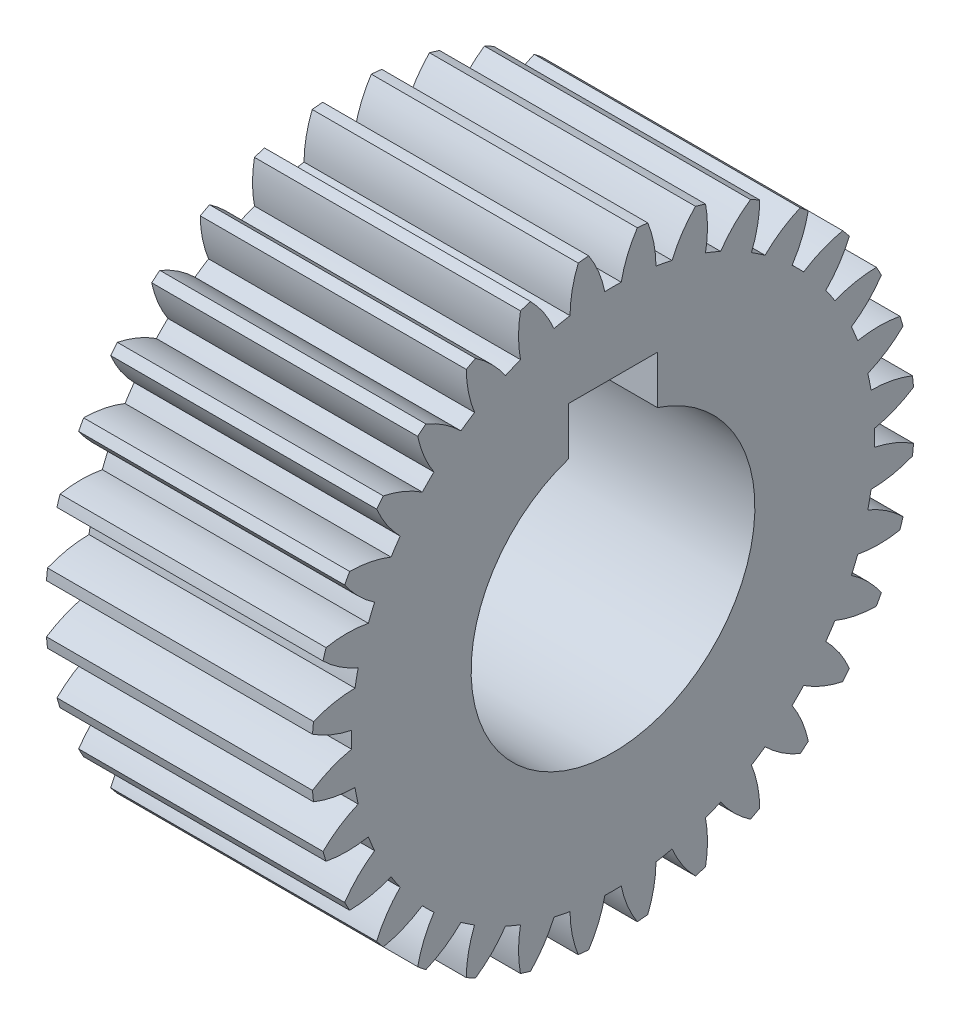
SolidWorks part; units mm, degrees
ref_plane "Plane1" through (0, 0, 0) normal (0, 0, 1) x (1, 0, 0)
ref_plane "Plane2" through (0, 0, 0) normal (0, 1, 0) x (1, 0, 0)
ref_plane "Plane3" through (0, 0, 0) normal (1, 0, 0) x (0, 0, -1)
sketch "HoldingSke" plane through (0, 0, 0) normal (0, 1, 0) x (1, 0, 0)
  line L0 (0, 0) -> (0.848, -0.5299)
  line L1 (-15, 0) -> (100, 0) construction
  line L2 (0, 0) -> (-2.1039, 2.3779)
  line L3 (0, 0) -> (-11.863, 4.5341)
  line L4 (0, 0) -> (7.3237, 4.5764)
  line L5 (0, 0) -> (-46.8476, -17.4728)
  line L6 (0, 0) -> (-12.4344, -8.3896)
  line L7 (-2.1039, 2.3779) -> (8.6586, 51.2059)
  line L8 (-76.2, 54.61) -> (-73.9, 54.61)
  line L9 (-71.009, 38.7566) -> (-53.1078, 45.2721)
  line L10 (-76.2, 71.12) -> (104.1128, 71.12)
  line L11 (0, 0) -> (-15, 0)
  line L12 (-76.2, 101.6) -> (-76.162, 101.6)
  line L13 (24.9733, 27.94) -> (52.9518, 28.4284)
  line L14 (24.9733, 27.94) -> (24.9743, 27.94)
  line L15 (24.9733, 27.94) -> (100.4006, 29.5858)
  line L16 (-63.627, -1) -> (-12.827, -1)
  circle A0 centre (0, 0) radius 8
  circle A1 centre (0, 0) radius 14.749
  circle A2 centre (0, 0) radius 37.5
  circle A3 centre (0, 0) radius 8
  dimension "MHD" = 29.498
  dimension "Hub_dia" = 75
  dimension "Bore" = 16
  dimension "MBD" = 16
  dimension "Num_teeth" = 32
  dimension "Pitch" = 1
  dimension "Overall_len" = 50
  dimension "Show_teeth" = 32
  dimension "Thickness" = 15
  dimension "OAL" = 50.0001
  dimension "T_dim" = 2.3
  dimension "Ap" = 20
  dimension "H" = 19.05
  dimension "Pitch_radius" = 180.3128
  dimension "Width" = 15
  dimension "Backlash" = 0.038
  dimension "Addendum_fac" = 1
  dimension "Dedendum_fac" = 1.25
  dimension "Clearance_fac" = 0.25
  dimension "Dedendum_add" = 0.001
  dimension "Module" = 1
sketch "BasProSke" plane through (0, 0, 0) normal (0, 1, 0) x (1, 0, 0)
  line L0 (-10, 0) -> (60, 0) construction
  line L1 (0, 0) -> (0, 17)
  line L2 (0, 0) -> (15, 0)
  line L3 (15, 0) -> (15, 17)
  line L4 (15, 17) -> (0, 17)
  dimension "Thickness" = 15
  dimension "Diameter" = 34
revolve "Base-Revolve" add sketch "BasProSke" angle 360 about L0
sketch "TooCutSke" plane through (0, 0, 0) normal (1, 0, 0) x (0, 0, -1)
  line L1 (0, 0) -> (0, 107) construction
  line L2 (0, 0) -> (-0.8516, 15.9773) construction
  line L3 (0, 0) -> (-3.1334, 31.8138) construction
  line L4 (-0.8516, 15.9773) -> (-1.5667, 15.9069) construction
  arc A0 (0.462, 14.7418) -> (-0.462, 14.7418) centre (0, 0) ccw
  arc A1 (1.3867, 16.9688) -> (-1.3867, 16.9688) centre (0, 0) ccw
  circle A2 centre (0, 0) radius 16 construction
  circle A3 centre (0, 0) radius 15.0351 construction
  arc A4 (-0.462, 14.7418) -> (-1.3867, 16.9688) centre (-6.7293, 13.4451) ccw
  arc A5 (1.3867, 16.9688) -> (0.462, 14.7418) centre (6.7293, 13.4451) ccw
  dimension "Root_dia" = 29.498
  dimension "Overcut_dia" = 34.0508
  dimension "Pitch_dia" = 32
  dimension "Base_dia" = 30.0702
  dimension "Flank_rad" = 6.4
  dimension "Half_ang" = 5.625
  dimension "Half_CT" = 0.7186
extrude "ToothCut" cut sketch "TooCutSke" along normal through all
fillet "Breaks" [suppressed] radius 0.02
fillet "RootFillets" [suppressed] radius 0.251
pattern_circular "TeethCuts" count 32 every 11.25 about axis through (-10, 0, 0) along (1, 0, 0) of "ToothCut", "RootFillets", "Breaks"
sketch "HubNeaOneSke" plane through (0, 0, 0) normal (-1, 0, 0) x (0, 0, 1)
  circle A0 centre (0, 0) radius 14.749
  dimension "Diameter" = 29.498
extrude "HubNearOne" [suppressed] add sketch "HubNeaOneSke" along normal blind 35.0001
sketch "HubNeaBotSke" plane through (0, 0, 0) normal (-1, 0, 0) x (0, 0, 1)
  circle A0 centre (0, 0) radius 14.749
  dimension "Diameter" = 29.498
extrude "HubNearBoth" [suppressed] add sketch "HubNeaBotSke" along normal blind 17.5
ref_plane "FarPln" through (15, 0, 0) normal (1, 0, 0) x (0, 0, -1)
sketch "HubFarSke" plane through (15, 0, 0) normal (1, 0, 0) x (0, 0, -1)
  circle A0 centre (0, 0) radius 14.749
  dimension "Diameter" = 29.498
extrude "HubFar" [suppressed] add sketch "HubFarSke" along normal blind 17.5
sketch "BorSke" plane through (0, 0, 0) normal (1, 0, 0) x (0, 0, -1)
  circle A0 centre (0, 0) radius 8
  dimension "Diameter" = 16
extrude "Bore" cut sketch "BorSke" along normal mid plane 100.0001
sketch "KeySke" plane through (0, 0, 0) normal (1, 0, 0) x (0, 0, -1)
  line L0 (-2.5, 0) -> (-2.5, 10.3)
  line L1 (-2.5, 10.3) -> (2.5, 10.3)
  line L2 (2.5, 10.3) -> (2.5, 0)
  line L3 (0, 0) -> (0, 34) construction
  line L4 (-2.5, 0) -> (2.5, 0)
  dimension "Offset" = 10.3
  dimension "Width" = 5
extrude "Keyway" cut sketch "KeySke" along normal mid plane 100.0001
pattern_circular "Keyway2" [suppressed] count 2 every 90 about axis through (-10, 0, 0) along (1, 0, 0)
equation "' \"Module@HoldingSke\" = 6.35"
equation "' \"Num_teeth@HoldingSke\" = 12"
equation "' \"Ap@HoldingSke\" =  20"
equation "' \"Ap@HoldingSke\" = 20"
equation "' \"Width@HoldingSke\" = 0.5 * 25.4"
equation "' \"Hub_dia@HoldingSke\"= 1 * 25.4"
equation "' \"Hub_dia@HoldingSke\" = 1 * 25.4"
equation "' \"Overall_len@HoldingSke\" = 1.0 * 25.4"
equation "' \"Bore@HoldingSke\" = 0.75 * 25.4"
equation "' \"T_dim@HoldingSke\" = 0.1 * 25.4"
equation "' \"Width@KeySke\" = 0.25 * 25.4"
equation "' \"Show_teeth@HoldingSke\" = 13"
equation "' \"Backlash@HoldingSke\" = 0.009 * 25.4"
equation "' \"Addendum_fac@HoldingSke\" = 1.0"
equation "' \"Dedendum_fac@HoldingSke\" = 1.25"
equation "' \"Dedendum_add@HoldingSke\" = 0.00005 * 25.4"
equation "' \"Clearance_fac@HoldingSke\" = 0.25"
equation "\"Pitch@HoldingSke\" = 1 / \"Module@HoldingSke\""
equation "\"Overcut_dia@TooCutSke\" = (\"Num_teeth@HoldingSke\" + 2 * \"Addendum_fac@HoldingSke\") / \"Pitch@HoldingSke\" + 0.002 * 25.4"
equation "\"Pitch_dia@TooCutSke\" = \"Num_teeth@HoldingSke\" / \"Pitch@HoldingSke\""
equation "\"Base_dia@TooCutSke\" = \"Num_teeth@HoldingSke\" / \"Pitch@HoldingSke\" * cos((\"Ap@HoldingSke\"  * 3.14159265 / 180))"
equation "\"Root_dia@TooCutSke\" = (\"Num_teeth@HoldingSke\" + 2) / \"Pitch@HoldingSke\" - 2 * (\"Addendum_fac@HoldingSke\" + \"Dedendum_fac@HoldingSke\") / \"Pitch@HoldingSke\" - \"Dedendum_add@HoldingSke\" * 2"
equation "\"Half_ang@TooCutSke\" = 180 / \"Num_teeth@HoldingSke\""
equation "\"Half_CT@TooCutSke\" = \"Num_teeth@HoldingSke\" / \"Pitch@HoldingSke\" * sin((3.14159265 / 2 / \"Num_teeth@HoldingSke\")) / 2 - 7 * \"Backlash@HoldingSke\" / 4"
equation "\"Flank_rad@TooCutSke\" = \"Num_teeth@HoldingSke\" / \"Pitch@HoldingSke\" / 5"
equation "\"Radius@RootFillets\" = \"Clearance_fac@HoldingSke\" / \"Pitch@HoldingSke\" + \"Dedendum_add@HoldingSke\""
equation "\"Break_rad@Breaks\" = 0.02 / \"Pitch@HoldingSke\""
equation "\"Thickness@HoldingSke\" = \"Width@HoldingSke\""
equation "\"OAL@HoldingSke\" = \"Thickness@HoldingSke\""
equation "\"MHD@HoldingSke\" = (\"Num_teeth@HoldingSke\" + 2) / \"Pitch@HoldingSke\" - 2 * (\"Addendum_fac@HoldingSke\" + \"Dedendum_fac@HoldingSke\")  / \"Pitch@HoldingSke\" - \"Dedendum_add@HoldingSke\" * 2"
equation "\"MBD@HoldingSke\" = (\"Num_teeth@HoldingSke\" + 2) / \"Pitch@HoldingSke\" - 2 * (\"Addendum_fac@HoldingSke\" + \"Dedendum_fac@HoldingSke\")  / \"Pitch@HoldingSke\" - \"Dedendum_add@HoldingSke\" * 2 - 0.002 * 25.4"
equation "\"MHD@HoldingSke\" = ((sgn( \"MHD@HoldingSke\" - \"Hub_dia@HoldingSke\" )-1)*( \"MHD@HoldingSke\" - \"Hub_dia@HoldingSke\" ))/-2+ \"Hub_dia@HoldingSke\""
equation "\"MBD@HoldingSke\" = ((sgn( \"MBD@HoldingSke\" - \"Bore@HoldingSke\" )-1)*( \"MBD@HoldingSke\" - \"Bore@HoldingSke\" ))/-2+ \"Bore@HoldingSke\""
equation "\"OAL@HoldingSke\" = ((sgn( \"OAL@HoldingSke\" - \"Overall_len@HoldingSke\" )+1)*( \"OAL@HoldingSke\" - \"Overall_len@HoldingSke\" ))/2 + \"Overall_len@HoldingSke\" + 0.000002 * 25.4"
equation "\"Num_teeth@TeethCuts\" = int( \"Show_teeth@HoldingSke\" ) + 1"
equation "\"Num_teeth@TeethCuts\" = ((sgn( \"Num_teeth@TeethCuts\" - \"Num_teeth@HoldingSke\" )-1)*( \"Num_teeth@TeethCuts\" - \"Num_teeth@HoldingSke\" ))/-2+ \"Num_teeth@HoldingSke\""
equation "\"Num_teeth@TeethCuts\" = ((sgn( \"Num_teeth@TeethCuts\" - 2.0)+1)*( \"Num_teeth@TeethCuts\" - 2.0))/2 +2.0"
equation "\"Angle@TeethCuts\" = 360.0 / \"Num_teeth@HoldingSke\""
equation "\"Diameter@BasProSke\" = (\"Num_teeth@HoldingSke\" + 2 * \"Addendum_fac@HoldingSke\") / \"Pitch@HoldingSke\""
equation "\"Thickness@BasProSke\"  = \"Thickness@HoldingSke\""
equation "' \"Fillet_rad@BasProSke\" =  \"Thickness@HoldingSke\" * 0.05"
equation "' \"Fillet_rad@BasProSke\" = \"Thickness@HoldingSke\" * 0.05"
equation "\"MHD@HoldingSke\" = ((sgn( \"MHD@HoldingSke\" - \"Root_dia@TooCutSke\" )-1)*( \"MHD@HoldingSke\" - \"Root_dia@TooCutSke\" ))/-2+ \"Root_dia@TooCutSke\""
equation "\"Diameter@HubNeaOneSke\" = \"MHD@HoldingSke\""
equation "\"Length@HubNearOne\" = \"OAL@HoldingSke\" - \"Thickness@BasProSke\""
equation "\"Diameter@HubNeaBotSke\" = \"MHD@HoldingSke\""
equation "\"Length@HubNearBoth\" = ( \"OAL@HoldingSke\" - \"Thickness@BasProSke\" ) / 2.0"
equation "\"Thickness@FarPln\" = \"Thickness@BasProSke\""
equation "\"Diameter@HubFarSke\" = \"MHD@HoldingSke\""
equation "\"Length@HubFar\" = ( \"OAL@HoldingSke\" - \"Thickness@BasProSke\" ) / 2.0"
equation "\"Diameter@BorSke\" = \"MBD@HoldingSke\""
equation "\"D1@Bore\" = \"OAL@HoldingSke\" * 2.0"
equation "\"D1@Keyway\" = \"OAL@HoldingSke\" * 2.0"
equation "\"Offset@KeySke\" = \"T_dim@HoldingSke\" + \"MBD@HoldingSke\" / 2.0"
